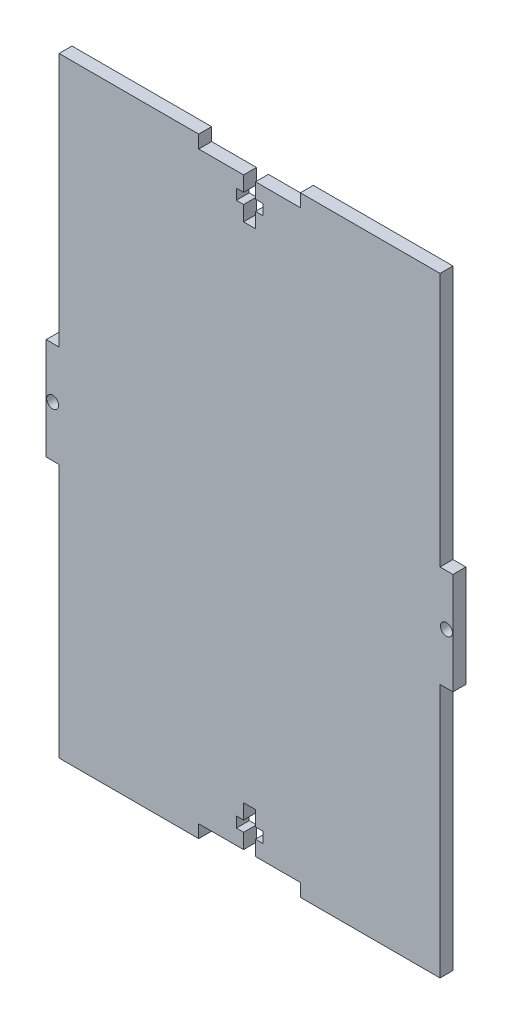
SolidWorks part; units mm, degrees
ref_plane "Front Plane" through (0, 0, 0) normal (0, 0, 1) x (1, 0, 0)
ref_plane "Top Plane" through (0, 0, 0) normal (0, 1, 0) x (1, 0, 0)
ref_plane "Right Plane" through (0, 0, 0) normal (1, 0, 0) x (0, 0, -1)
sketch "Sketch1" plane through (0, 0, 0) normal (0, 0, 1) x (1, 0, 0)
  line L0 (0, 75) -> (0, -75) construction
  line L1 (-46.825, 75) -> (46.825, 75)
  line L2 (-46.825, 75) -> (-46.825, -75)
  line L3 (-46.825, -75) -> (46.825, -75)
  line L4 (46.825, 75) -> (46.825, -75)
  line L5 (-46.825, 75) -> (46.825, -75) construction
  line L6 (-46.825, -75) -> (46.825, 75) construction
  line L7 (-46.825, 0) -> (46.825, 0) construction
  line L8 (-3.25, -65.525) -> (3.25, -65.525)
  line L9 (12.5, 75) -> (-12.5, 75)
  line L10 (12.5, 75) -> (12.5, 71.825)
  line L11 (12.5, 71.825) -> (-12.5, 71.825)
  line L12 (-12.5, 75) -> (-12.5, 71.825)
  line L13 (12.5, 75) -> (-12.5, 71.825) construction
  line L14 (12.5, 71.825) -> (-12.5, 75) construction
  line L15 (-1.47, 71.825) -> (1.47, 71.825)
  line L16 (-1.47, 71.825) -> (-1.47, 61.825)
  line L17 (-1.47, 61.825) -> (1.47, 61.825)
  line L18 (1.47, 71.825) -> (1.47, 61.825)
  line L19 (-1.47, 71.825) -> (1.47, 61.825) construction
  line L20 (-1.47, 61.825) -> (1.47, 71.825) construction
  line L21 (-3.25, 68.125) -> (3.25, 68.125)
  line L22 (-3.25, 68.125) -> (-3.25, 65.525)
  line L23 (-3.25, 65.525) -> (3.25, 65.525)
  line L24 (3.25, 68.125) -> (3.25, 65.525)
  line L25 (-3.25, 68.125) -> (3.25, 65.525) construction
  line L26 (-3.25, 65.525) -> (3.25, 68.125) construction
  line L27 (3.25, -68.125) -> (3.25, -65.525)
  line L28 (-3.25, -68.125) -> (3.25, -68.125)
  line L29 (-3.25, -68.125) -> (-3.25, -65.525)
  line L30 (-1.47, -61.825) -> (1.47, -61.825)
  line L31 (1.47, -71.825) -> (1.47, -61.825)
  line L32 (-1.47, -71.825) -> (1.47, -71.825)
  line L33 (-1.47, -71.825) -> (-1.47, -61.825)
  line L34 (12.5, -71.825) -> (-12.5, -71.825)
  line L35 (-12.5, -75) -> (-12.5, -71.825)
  line L36 (12.5, -75) -> (-12.5, -75)
  line L37 (12.5, -75) -> (12.5, -71.825)
  line L38 (50, -12.5) -> (46.825, -12.5)
  line L39 (-50, 12.5) -> (-46.825, 12.5)
  line L40 (-50, 12.5) -> (-50, -12.5)
  line L41 (-50, -12.5) -> (-46.825, -12.5)
  line L42 (-46.825, 12.5) -> (-46.825, -12.5)
  line L43 (-50, 12.5) -> (-46.825, -12.5) construction
  line L44 (-50, -12.5) -> (-46.825, 12.5) construction
  line L45 (46.825, 12.5) -> (46.825, -12.5)
  line L46 (50, 12.5) -> (46.825, 12.5)
  line L47 (50, 12.5) -> (50, -12.5)
  circle A0 centre (-48.4125, 0) radius 1.47
  circle A1 centre (48.4125, 0) radius 1.47
  point P0 (0, 0)
  point P10 (0, 73.4125)
  point P15 (0, 66.825)
  point P20 (0, 66.825)
  point P37 (-48.4125, 0)
  dimension "D11" = 2.94
  dimension "D1" = 150
  dimension "D2" = 100
  dimension "D3" = 3.175
  dimension "D4" = 10
  dimension "D5" = 2.94
  dimension "D6" = 25
  dimension "D7" = 6.5
  dimension "D8" = 2.6
  dimension "D9" = 6.3
  dimension "D10" = 3.175
extrude "Boss-Extrude1" add sketch "Sketch1" along normal mid plane 3.175 contours L21 L24 L23 L18 L17 L16 L22 L11 L12 L1 L2 L3 L4 L10 | L40 L39 L42 L41 | A0 | L38 L45 L46 L47 | A1
